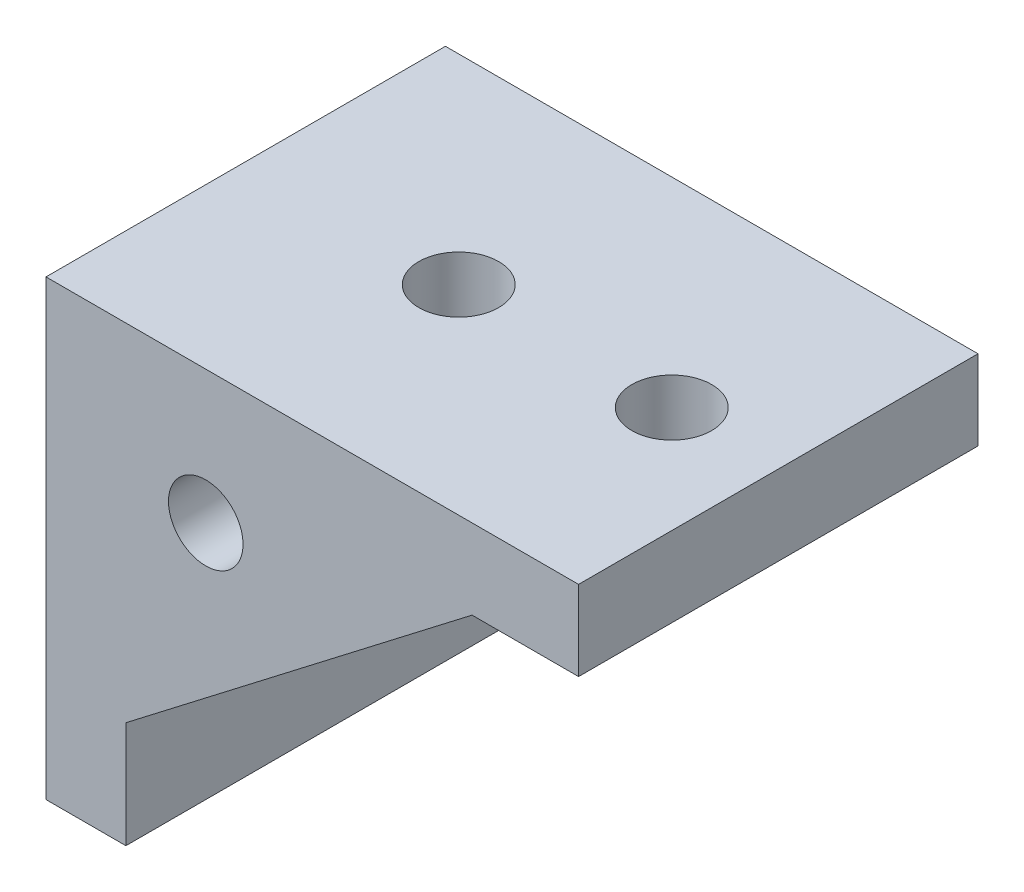
SolidWorks part; units mm, degrees
material "PLA"
ref_plane "前视基准面" through (0, 0, 0) normal (0, 0, 1) x (1, 0, 0)
ref_plane "上视基准面" through (0, 0, 0) normal (0, 1, 0) x (1, 0, 0)
ref_plane "右视基准面" through (0, 0, 0) normal (1, 0, 0) x (0, 0, -1)
sketch "草图1" plane through (0, 0, 0) normal (0, 0, 1) x (1, 0, 0)
  line L0 (0, 35.4185) -> (0, -34.1212) construction
  line L1 (-38.143, 0) -> (49.041, 0) construction
  line L2 (0, -14) -> (0, 0)
  line L3 (0, 0) -> (17, 0)
  line L4 (17, 0) -> (17, 3)
  line L5 (17, 3) -> (-3, 3)
  line L6 (-3, 3) -> (-3, -14)
  line L7 (-3, -14) -> (0, -14)
  dimension "D1" = 3
  dimension "D2" = 3
  dimension "D3" = 17
  dimension "D4" = 17
extrude "凸台-拉伸1" add sketch "草图1" along normal blind 15
sketch "草图2" plane through (0, 0, 0) normal (1, 0, 0) x (0, 0, -1)
  line L0 (-7.5, -20.192) -> (-7.5, 12.8252) construction
  line L1 (-15, -14) -> (-15, 0) construction
  line L3 (-15, -14) -> (0, -14) construction
  circle A1 centre (-7.5, -6) radius 1.5
  dimension "D2" = 8
  dimension "D3" = 3
  dimension "D1" = 7.5
extrude "切除-拉伸1" cut sketch "草图2" against normal blind 3
sketch "草图3" plane through (0, 0, 0) normal (0, -1, 0) x (1, 0, 0)
  line L0 (22.5314, 7.5) -> (-12.483, 7.5) construction
  line L1 (0, 15) -> (17, 15) construction
  line L2 (0, 15) -> (0, 0) construction
  circle A0 centre (13, 7.5) radius 1.5
  circle A1 centre (5, 7.5) radius 1.5
  dimension "D2" = 3
  dimension "D4" = 8
  dimension "D1" = 7.5
  dimension "D3" = 5
extrude "切除-拉伸2" cut sketch "草图3" against normal blind 3
sketch "草图4" plane through (0, 0, 15) normal (0, 0, 1) x (1, 0, 0)
  line L0 (0, 0) -> (0, -10)
  line L1 (0, -14) -> (0, 0) construction
  line L2 (0, 0) -> (13, 0)
  line L3 (0, 0) -> (17, 0) construction
  line L4 (13, 0) -> (0, -10)
  dimension "D1" = 13
  dimension "D2" = 10
extrude "凸台-拉伸2" add sketch "草图4" against normal blind 2
sketch "草图5" plane through (0, 0, 0) normal (0, 0, -1) x (-1, 0, 0)
  line L3 (0, 0) -> (-13, 0)
  line L4 (-13, 0) -> (0, -10)
  line L5 (0, -10) -> (0, 0)
  line L6 (0, 0) -> (-13, 0)
  line L7 (-13, 0) -> (0, -10)
  line L8 (0, -10) -> (0, 0)
  dimension "D1" = 0
extrude "凸台-拉伸3" add sketch "草图5" against normal blind 2
sketch "草图6" plane through (0, 0, 0) normal (0, 0, -1) x (-1, 0, 0)
  line L0 (3, 3) -> (3, -14) construction
  line L1 (-17, 3) -> (3, 3) construction
  circle A0 centre (-3, -2) radius 1.4
  dimension "D1" = 2.8
  dimension "D2" = 6
  dimension "D3" = 5
extrude "切除-拉伸3" cut sketch "草图6" against normal through all
fillet "圆角1" radius 3 1 edges at (0, 0, 7.5)
